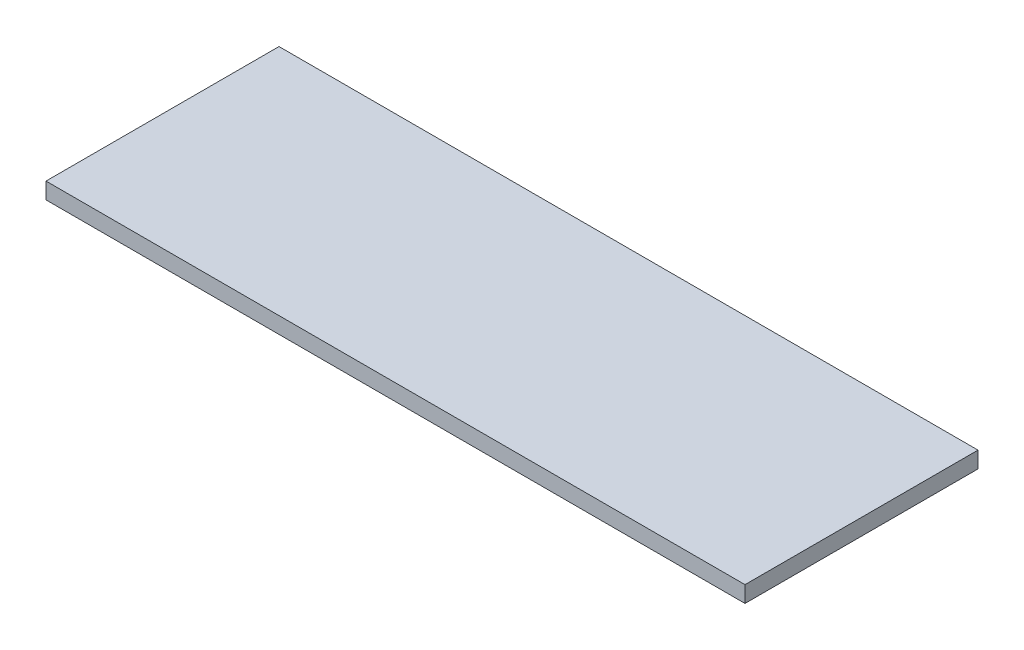
SolidWorks part; units mm, degrees
ref_plane "Front Plane" through (0, 0, 0) normal (0, 0, 1) x (1, 0, 0)
ref_plane "Top Plane" through (0, 0, 0) normal (0, 1, 0) x (1, 0, 0)
ref_plane "Right Plane" through (0, 0, 0) normal (1, 0, 0) x (0, 0, -1)
sketch "Sketch1" plane through (0, 0, 0) normal (0, 1, 0) x (1, 0, 0)
  line L1 (-15, -5) -> (15, -5)
  line L2 (-15, -5) -> (-15, 5)
  line L3 (-15, 5) -> (15, 5)
  line L4 (15, -5) -> (15, 5)
  line L5 (-15, -5) -> (15, 5) construction
  line L6 (-15, 5) -> (15, -5) construction
  point P0 (0, 0)
  dimension "D1" = 10
  dimension "D2" = 30
extrude "Boss-Extrude1" add sketch "Sketch1" along normal blind 0.7
